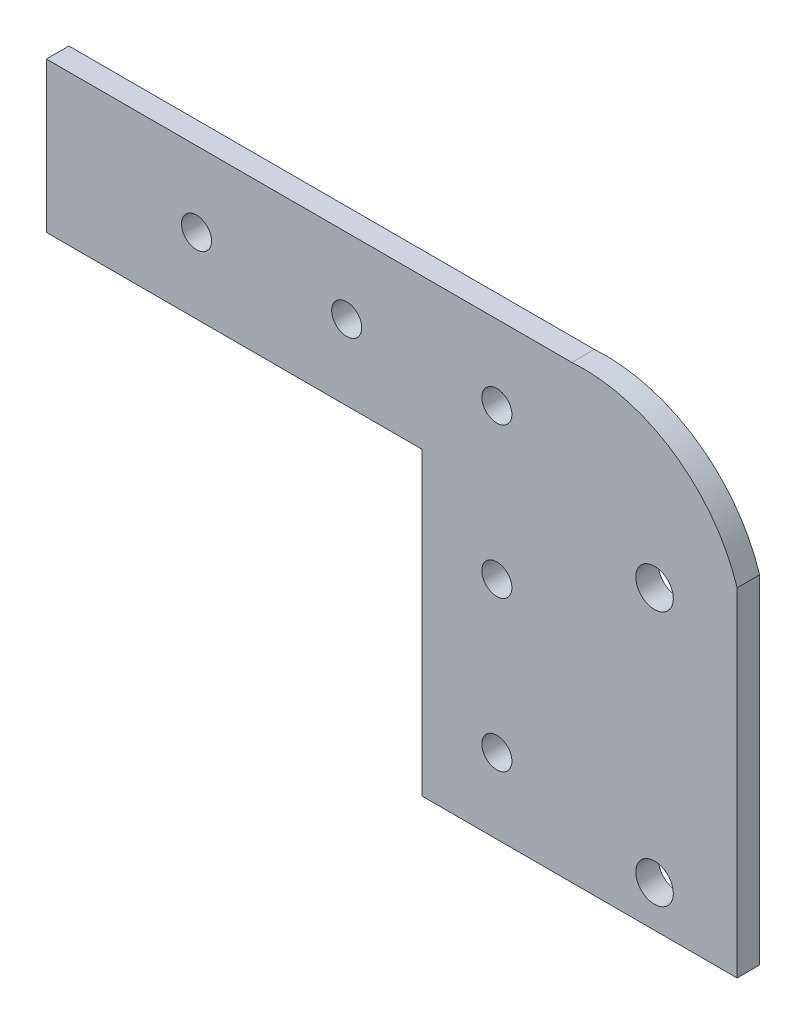
SolidWorks part; units mm, degrees
ref_plane "前视基准面" through (0, 0, 0) normal (0, 0, 1) x (1, 0, 0)
ref_plane "上视基准面" through (0, 0, 0) normal (0, 1, 0) x (1, 0, 0)
ref_plane "右视基准面" through (0, 0, 0) normal (1, 0, 0) x (0, 0, -1)
sketch "草图1" plane through (0, 0, 0) normal (0, 0, 1) x (1, 0, 0)
  line L1 (-30, -70) -> (-10, -70)
  line L2 (-10, -70) -> (-10, -30)
  line L3 (-10, -30) -> (-80, -30)
  line L4 (-80, -30) -> (-80, -10)
  line L6 (-10, -30) -> (-10, -28.2843)
  line L7 (-30, -70) -> (-30, 0)
  line L8 (-80, -10) -> (-28.2843, -10)
  line L9 (-28.2843, -10) -> (-10, -10)
  line L10 (-10, -70) -> (12, -70)
  line L11 (-10, -70) -> (-10, -25)
  line L12 (-10, -25) -> (12, -25)
  line L13 (12, -70) -> (12, -25)
  line L14 (-10, -10) -> (-10, -25)
  line L15 (1, -25) -> (1, -70) construction
  circle A0 centre (0, 0) radius 30
  circle A1 centre (0, 0) radius 4
  circle A2 centre (1, -64.5) radius 2.5
  circle A3 centre (1, -30.5) radius 2.5
  point P22 (1, -47.5)
  dimension "D1" = 60
  dimension "D5" = 8
  dimension "D8" = 5
  dimension "D9" = 5
  dimension "D11" = 34
  dimension "D12" = 60
  dimension "D2" = 20
  dimension "D3" = 20
  dimension "D4" = 70
  dimension "D6" = 45
  dimension "D7" = 22
  dimension "D10" = 17
extrude "凸台-拉伸1" add sketch "草图1" along normal blind 3 contours L7 L1 L2 L3 | L15 A3 A0 L6 L2 L10 A2 | A3 L15 A2 L10 L13 A0 | L15 L12 L11 A0 A3 | L12 L15 A3 A0 L13 | A0 L8 L7 L3 L6 | L9 A0 L11 L14 | L8 L4 L3 L7
sketch "草图2" plane through (0, 0, 0) normal (0, 0, -1) x (-1, 0, 0)
  line L0 (20, -20) -> (20, -50020) construction
  line L1 (20, -20) -> (50020, -20) construction
  circle A0 centre (20, -40) radius 2 construction
  circle A1 centre (40, -20) radius 2 construction
  circle A2 centre (20, -20) radius 2 construction
  circle A3 centre (20, -40) radius 2
  circle A4 centre (40, -20) radius 2
  circle A5 centre (20, -20) radius 2
  circle A6 centre (20, -60) radius 2
  circle A7 centre (60, -20) radius 2
  dimension "D1" = 4
  dimension "D2" = 4
  dimension "D3" = 20
  dimension "D4" = 20
extrude "切除-拉伸1" cut sketch "草图2" against normal blind 10
sketch "草图3" plane through (0, 0, 3) normal (0, 0, 1) x (1, 0, 0)
  line L0 (-10, -25) -> (12, -25) construction
  line L1 (-10, -25) -> (-10, -10) construction
  line L2 (-10, -25) -> (12, -25)
  line L3 (-10, -25) -> (-10, -10)
  arc A0 (12, -25) -> (-10, -10) centre (-8.527, -31.473) ccw
extrude "凸台-拉伸2" add sketch "草图3" against normal blind 3
